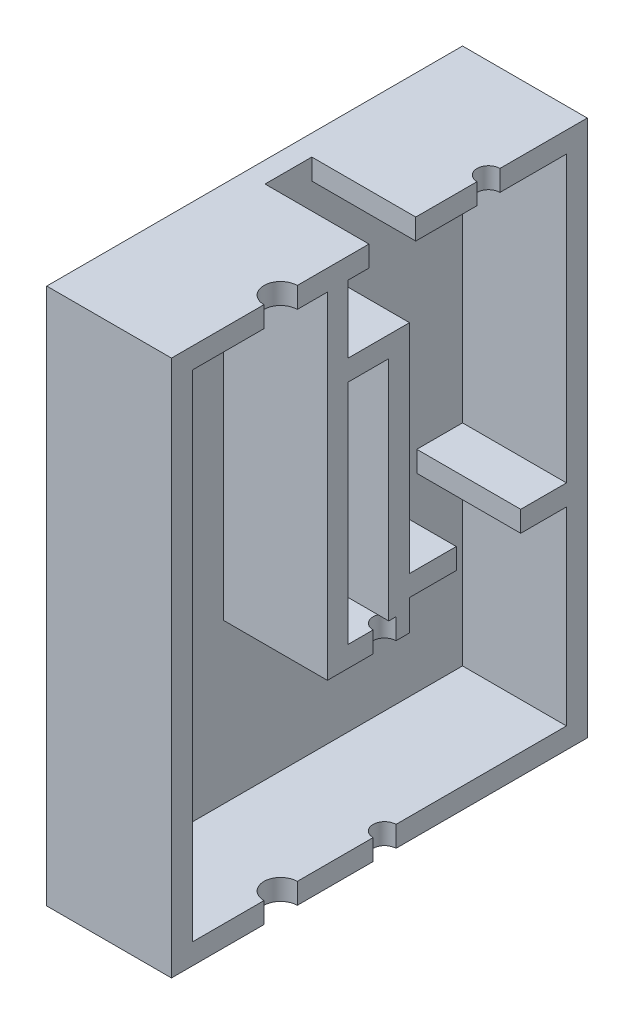
SolidWorks part; units mm, degrees
ref_plane "前视基准面" through (0, 0, 0) normal (0, 0, 1) x (1, 0, 0)
ref_plane "上视基准面" through (0, 0, 0) normal (0, 1, 0) x (1, 0, 0)
ref_plane "右视基准面" through (0, 0, 0) normal (1, 0, 0) x (0, 0, -1)
other "Configuration Table"
sketch "草图1" plane through (0, 0, 0) normal (1, 0, 0) x (0, 0, -1)
  line L1 (-20, 25.825) -> (20, 25.825)
  line L2 (-20, 25.825) -> (-20, -25.825)
  line L3 (-20, -25.825) -> (20, -25.825)
  line L4 (20, 25.825) -> (20, -25.825)
  line L5 (-20, 25.825) -> (20, -25.825) construction
  line L6 (-20, -25.825) -> (20, 25.825) construction
  point P0 (0, 0)
  dimension "D1" = 51.65
  dimension "D2" = 40
extrude "凸台-拉伸1" add sketch "草图1" along normal blind 12
shell "抽壳1" thickness 2
sketch "草图3" plane through (2, 0, 0) normal (1, 0, 0) x (0, 0, -1)
  line L3 (2.9, -8.525) -> (-5, -8.525)
  line L13 (2.9, -5.575) -> (2.9, -8.525) construction
  line L55 (18, 23.825) -> (-18, 23.825) construction
  line L58 (0.9, 15.325) -> (0.9, -6.525) construction
  line L65 (18, -23.825) -> (18, 23.825) construction
  line L66 (13.6, -5.575) -> (13.6, -3.575) construction
  line L67 (7.4, -3.575) -> (7.4, -5.575) construction
  line L68 (7.4, -5.575) -> (2.9, -5.575) construction
  line L69 (18, -5.575) -> (13.6, -5.575) construction
  line L70 (13.6, -3.575) -> (18, -3.575) construction
  line L71 (2.9, -3.575) -> (7.4, -3.575) construction
  line L72 (2.9, 17.325) -> (2.9, -3.575) construction
  line L73 (-3, 17.325) -> (2.9, 17.325) construction
  line L74 (-3, 15.325) -> (0.9, 15.325) construction
  line L76 (-3, 23.825) -> (-3, 17.325) construction
  line L77 (-3, -6.525) -> (-3, 15.325) construction
  line L81 (2.9, -5.575) -> (2.9, -8.525)
  line L85 (18, -5.575) -> (18, -3.575)
  line L86 (13.6, -5.575) -> (13.6, -3.575)
  line L87 (7.4, -3.575) -> (7.4, -5.575)
  line L88 (7.4, -5.575) -> (2.9, -5.575)
  line L89 (18, -5.575) -> (13.6, -5.575)
  line L90 (13.6, -3.575) -> (18, -3.575)
  line L91 (2.9, -3.575) -> (7.4, -3.575)
  line L92 (2.9, 17.325) -> (2.9, -3.575)
  line L93 (-3, 17.325) -> (2.9, 17.325)
  line L94 (-3, 15.325) -> (0.9, 15.325)
  line L96 (-3, 23.825) -> (-3, 17.325)
  line L97 (-3, -6.525) -> (-3, 15.325)
  line L99 (0.9, -6.525) -> (-3, -6.525) construction
  line L101 (-5, -8.525) -> (-5, 23.825) construction
  line L102 (-3, 23.825) -> (-5, 23.825)
  line L103 (0.9, 15.325) -> (0.9, -6.525)
  line L104 (0.9, -6.525) -> (-3, -6.525)
  line L106 (-5, -8.525) -> (-5, 23.825)
extrude "凸台-拉伸6" add sketch "草图3" along normal up to surface (10 mm away) up to face at (12, 0, 0)
sketch "草图4" plane through (0, 25.825, 0) normal (0, 1, 0) x (1, 0, 0)
  line L0 (12, 20) -> (12, -20) construction
  line L1 (12, -1) -> (2, -1)
  line L2 (12, -1) -> (12, 3.5)
  line L3 (12, 3.5) -> (2, 3.5)
  line L4 (2, -1) -> (2, 3.5)
  line L5 (2, 18) -> (2, -3) construction
  line L6 (16, 3) -> (8, 3) construction
  line L7 (8, 0) -> (4, 0) construction
  circle A0 centre (12, 10.5) radius 1.1
  circle A1 centre (12, 10.5) radius 1 construction
  circle A2 centre (12, -9.5) radius 1.6
  circle A3 centre (12, -9.5) radius 1.5 construction
  dimension "D3" = 0.1
  dimension "D4" = 0.1
  dimension "D1" = 0.5
  dimension "D2" = 1
extrude "切除-拉伸1" cut sketch "草图4" against normal up to next and the other way through all
sketch "草图6" plane through (0, -25.825, 0) normal (0, -1, 0) x (1, 0, 0)
  circle A0 centre (12, -0.5) radius 1.1
  circle A1 centre (12, 9.5) radius 1.6
  arc A2 (12, 11.1) -> (12, 7.9) centre (12, 9.5) ccw construction
  arc A3 (12, -1.6) -> (12, 0.6) centre (12, -0.5) ccw construction
extrude "切除-拉伸4" cut sketch "草图6" against normal blind 19.3
